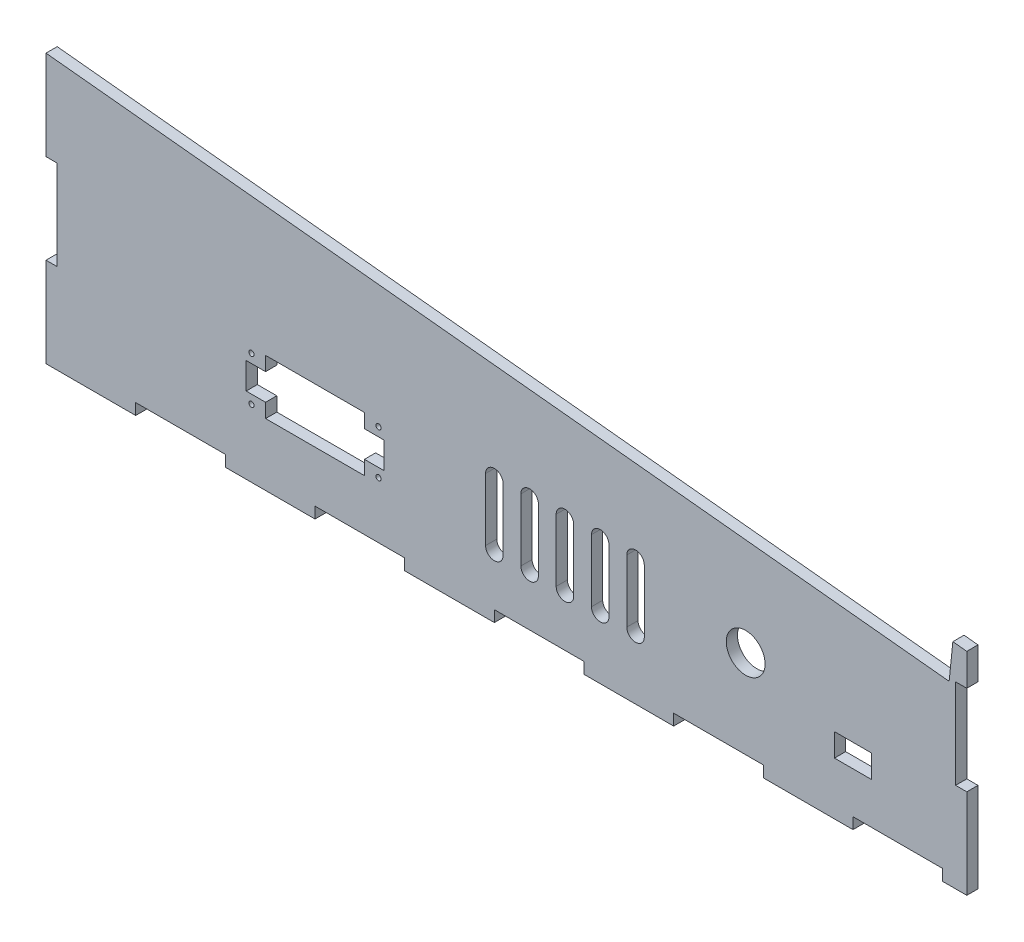
SolidWorks part; units mm, degrees
ref_plane "Front Plane" through (0, 0, 0) normal (0, 0, 1) x (1, 0, 0)
ref_plane "Top Plane" through (0, 0, 0) normal (0, 1, 0) x (1, 0, 0)
ref_plane "Right Plane" through (0, 0, 0) normal (1, 0, 0) x (0, 0, -1)
sketch "Sketch2" plane through (0, 0, 0) normal (0, 0, 1) x (1, 0, 0)
  line L0 (0, 152.4) -> (511.6739, 100)
  line L1 (0, 0) -> (511.6739, 0) construction
  line L2 (0, 0) -> (0, 152.4) construction
  line L4 (511.6739, 0) -> (511.6739, 100) construction
  line L5 (521.6739, 0) -> (521.6739, 50.8)
  line L6 (521.6739, 50.8) -> (515.3239, 50.8)
  line L7 (511.6739, 100) -> (513.7769, 120.5354)
  line L8 (513.7769, 120.5354) -> (521.6739, 119.7267)
  line L9 (521.6739, 119.7267) -> (521.6739, 0) construction
  line L10 (521.6739, 0) -> (511.6739, 0) construction
  line L11 (0, 0) -> (50.8, 0)
  line L12 (50.8, 0) -> (50.8, 6.35)
  line L13 (50.8, 6.35) -> (101.6, 6.35)
  line L14 (101.6, 6.35) -> (101.6, 0)
  line L15 (101.6, 0) -> (152.4, 0)
  line L16 (152.4, 0) -> (152.4, 6.35)
  line L17 (152.4, 6.35) -> (203.2, 6.35)
  line L18 (203.2, 6.35) -> (203.2, 0)
  line L19 (203.2, 0) -> (254, 0)
  line L20 (254, 0) -> (254, 6.35)
  line L21 (254, 6.35) -> (304.8, 6.35)
  line L22 (304.8, 6.35) -> (304.8, 0)
  line L23 (304.8, 0) -> (355.6, 0)
  line L24 (355.6, 0) -> (355.6, 6.35)
  line L25 (355.6, 6.35) -> (406.4, 6.35)
  line L26 (406.4, 6.35) -> (406.4, 0)
  line L27 (406.4, 0) -> (457.2, 0)
  line L28 (457.2, 0) -> (457.2, 6.35)
  line L29 (457.2, 6.35) -> (508, 6.35)
  line L30 (508, 6.35) -> (508, 0)
  line L31 (521.6739, 0) -> (508, 0)
  line L32 (515.3239, 50.8) -> (515.3239, 101.6)
  line L33 (515.3239, 101.6) -> (521.6739, 101.6)
  line L34 (521.6739, 101.6) -> (521.6739, 119.7267)
  line L35 (0, 50.8) -> (6.35, 50.8)
  line L36 (0, 50.8) -> (0, 0)
  line L37 (6.35, 50.8) -> (6.35, 101.6)
  line L38 (6.35, 101.6) -> (0, 101.6)
  line L42 (0, 101.6) -> (0, 254) construction
  line L44 (0, 101.6) -> (0, 152.4)
  line L45 (180.4, 58.3) -> (191.4, 58.3)
  line L46 (446.7, 42.85) -> (467.7, 42.85)
  line L47 (446.7, 42.85) -> (446.7, 29.85)
  line L48 (446.7, 29.85) -> (467.7, 29.85)
  line L49 (467.7, 42.85) -> (467.7, 29.85)
  line L50 (446.7, 42.85) -> (467.7, 29.85) construction
  line L51 (446.7, 29.85) -> (467.7, 42.85) construction
  line L52 (124.4, 66.3) -> (180.4, 66.3)
  line L53 (124.4, 66.3) -> (124.4, 58.3)
  line L54 (124.4, 35.3) -> (180.4, 35.3)
  line L55 (180.4, 66.3) -> (180.4, 58.3)
  line L56 (124.4, 66.3) -> (180.4, 35.3) construction
  line L57 (124.4, 35.3) -> (180.4, 66.3) construction
  line L58 (191.4, 58.3) -> (191.4, 43.3)
  line L59 (191.4, 43.3) -> (180.4, 43.3)
  line L60 (124.4, 58.3) -> (113.4, 58.3)
  line L61 (113.4, 58.3) -> (113.4, 43.3)
  line L62 (113.4, 43.3) -> (124.4, 43.3)
  line L63 (124.4, 43.3) -> (124.4, 35.3)
  line L64 (180.4, 43.3) -> (180.4, 35.3)
  line L65 (254, 35.3) -> (254, 70.6842) construction
  line L68 (249.0403, 35.3) -> (249.0403, 70.6842)
  line L71 (258.9597, 35.3) -> (258.9597, 70.6842)
  line L74 (274, 35.3) -> (274, 70.6842) construction
  line L77 (269.0403, 35.3) -> (269.0403, 70.6842)
  line L80 (278.9597, 35.3) -> (278.9597, 70.6842)
  line L83 (294, 35.3) -> (294, 70.6842) construction
  line L84 (289.0403, 35.3) -> (289.0403, 70.6842)
  line L85 (298.9597, 35.3) -> (298.9597, 70.6842)
  line L86 (314, 35.3) -> (314, 70.6842) construction
  line L87 (309.0403, 35.3) -> (309.0403, 70.6842)
  line L88 (318.9597, 35.3) -> (318.9597, 70.6842)
  line L89 (334, 35.3) -> (334, 70.6842) construction
  line L90 (329.0403, 35.3) -> (329.0403, 70.6842)
  line L91 (338.9597, 35.3) -> (338.9597, 70.6842)
  line L92 (6.35, 203.2) -> (0, 203.2) [skipped]
  line L93 (6.35, 152.4) -> (6.35, 203.2) [skipped]
  line L94 (0, 152.4) -> (6.35, 152.4) [skipped]
  circle A0 centre (396.4, 56.35) radius 11
  circle A1 centre (116.4, 63.3) radius 1.5
  circle A2 centre (188.4, 63.3) radius 1.5
  circle A3 centre (188.4, 38.3) radius 1.5
  circle A4 centre (116.4, 38.3) radius 1.5
  arc A7 (249.0403, 35.3) -> (258.9597, 35.3) centre (254, 35.3) ccw
  arc A8 (258.9597, 70.6842) -> (249.0403, 70.6842) centre (254, 70.6842) ccw
  arc A9 (269.0403, 35.3) -> (278.9597, 35.3) centre (274, 35.3) ccw
  arc A10 (278.9597, 70.6842) -> (269.0403, 70.6842) centre (274, 70.6842) ccw
  arc A11 (289.0403, 35.3) -> (298.9597, 35.3) centre (294, 35.3) ccw
  arc A12 (298.9597, 70.6842) -> (289.0403, 70.6842) centre (294, 70.6842) ccw
  arc A13 (309.0403, 35.3) -> (318.9597, 35.3) centre (314, 35.3) ccw
  arc A14 (318.9597, 70.6842) -> (309.0403, 70.6842) centre (314, 70.6842) ccw
  arc A15 (329.0403, 35.3) -> (338.9597, 35.3) centre (334, 35.3) ccw
  arc A16 (338.9597, 70.6842) -> (329.0403, 70.6842) centre (334, 70.6842) ccw
  point P6 (254, 52.9921)
  point P49 (457.2, 36.35)
  point P54 (152.4, 50.8)
  point P72 (0, 0)
  point P73 (457.2, 50.8)
  point P74 (274, 52.9921)
  point P81 (294, 52.9921)
  point P88 (314, 52.9921)
  point P95 (334, 52.9921)
  point P102 (0, 0)
  point P103 (0, 0)
  point P104 (0, 0)
  point P105 (0, 0)
  point P106 (0, 0)
  dimension "D14" = 22
  dimension "D23" = 3
  dimension "D32" = 5
  dimension "D33" = 50
  dimension "D1" = 514.35
  dimension "D2" = 100
  dimension "D3" = 10
  dimension "D4" = 50.8
  dimension "D5" = 6.35
  dimension "D6" = 50.8
  dimension "D8" = 6.35
  dimension "D9" = 50.8
  dimension "D10" = 50.8
  dimension "D11" = 50.8
  dimension "D12" = 6.35
  dimension "D15" = 21
  dimension "D16" = 13
  dimension "D17" = 56
  dimension "D18" = 31
  dimension "D19" = 11
  dimension "D20" = 11
  dimension "D21" = 15
  dimension "D22" = 15
  dimension "D24" = 3
  dimension "D25" = 3
  dimension "D26" = 3
  dimension "D27" = 3
  dimension "D28" = 3
  dimension "D29" = 3
  dimension "D30" = 3
  dimension "D31" = 3
  dimension "D34" = 10
  dimension "D35" = 30
  dimension "D7" = 5
  dimension "D13" = 2
extrude "Boss-Extrude1" add sketch "Sketch2" along normal blind 6.35
